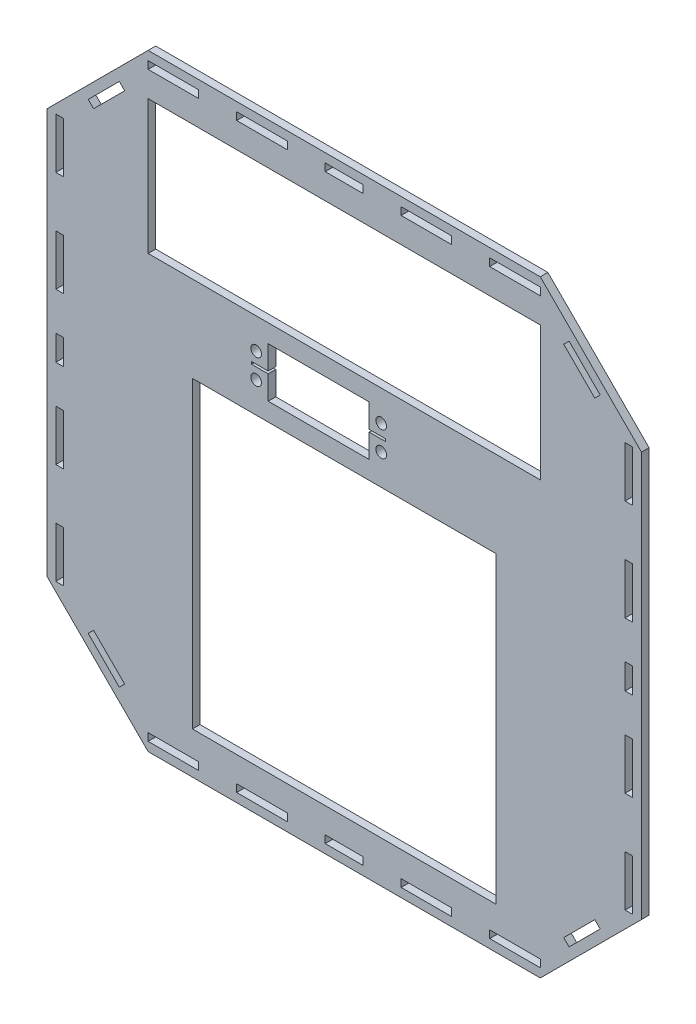
SolidWorks part; units mm, degrees
ref_plane "Přední rovina" through (0, 0, 0) normal (0, 0, 1) x (1, 0, 0)
ref_plane "Horní rovina" through (0, 0, 0) normal (0, 1, 0) x (1, 0, 0)
ref_plane "Pravá rovina" through (0, 0, 0) normal (1, 0, 0) x (0, 0, -1)
sketch "Skica2" plane through (0, 0, 0) normal (0, 0, 1) x (1, 0, 0)
  line L0 (-117.5, 80) -> (-77.5, 120)
  line L1 (-77.5, 120) -> (77.5, 120)
  line L2 (-117.5, 80) -> (-117.5, -80)
  line L3 (-77.5, -120) -> (77.5, -120)
  line L4 (117.5, 80) -> (117.5, -80)
  line L5 (-117.5, 120) -> (117.5, -120) construction
  line L6 (-117.5, -120) -> (117.5, 120) construction
  line L7 (77.5, 120) -> (117.5, 80)
  line L8 (77.5, -120) -> (117.5, -80)
  line L9 (-117.5, -80) -> (-77.5, -120)
  line L10 (0, 120) -> (0, -120) construction
  line L11 (-117.5, 0) -> (117.5, 0) construction
  line L21 (-111, 60) -> (-114, 60)
  line L22 (-114, 80) -> (-111, 80)
  line L23 (-114, 80) -> (-114, 60)
  line L25 (-111, 80) -> (-111, 60)
  line L26 (-114, 40) -> (-111, 40)
  line L27 (-114, 20) -> (-111, 20)
  line L28 (-114, 5) -> (-111, 5)
  line L29 (-111, 40) -> (-111, 20)
  line L30 (-114, 40) -> (-114, 20)
  line L31 (-111, 5) -> (-111, -5)
  line L32 (-114, 5) -> (-114, -5)
  line L33 (-114, -5) -> (-111, -5)
  line L34 (-114, -40) -> (-114, -20)
  line L35 (-114, -20) -> (-111, -20)
  line L36 (-111, -40) -> (-111, -20)
  line L37 (-114, -40) -> (-111, -40)
  line L38 (-114, -80) -> (-114, -60)
  line L39 (-111, -60) -> (-114, -60)
  line L40 (-111, -80) -> (-111, -60)
  line L41 (-114, -80) -> (-111, -80)
  line L42 (114, -80) -> (111, -80)
  line L43 (111, -80) -> (111, -60)
  line L44 (111, -60) -> (114, -60)
  line L45 (114, -80) -> (114, -60)
  line L46 (114, -40) -> (111, -40)
  line L47 (111, -40) -> (111, -20)
  line L48 (114, -20) -> (111, -20)
  line L49 (114, -40) -> (114, -20)
  line L50 (114, 5) -> (111, 5)
  line L51 (111, 5) -> (111, -5)
  line L52 (114, -5) -> (111, -5)
  line L53 (114, 5) -> (114, -5)
  line L54 (114, 40) -> (114, 20)
  line L55 (114, 20) -> (111, 20)
  line L56 (111, 40) -> (111, 20)
  line L57 (114, 40) -> (111, 40)
  line L58 (114, 80) -> (114, 60)
  line L59 (111, 60) -> (114, 60)
  line L60 (111, 80) -> (111, 60)
  line L61 (114, 80) -> (111, 80)
  line L62 (-57.5, 116.5) -> (-57.5, 113.5)
  line L63 (-77.5, 116.5) -> (-57.5, 116.5)
  line L64 (-77.5, 116.5) -> (-77.5, 113.5)
  line L65 (-77.5, 113.5) -> (-57.5, 113.5)
  line L67 (-42.5, 116.5) -> (-42.5, 113.5)
  line L68 (-22.5, 116.5) -> (-22.5, 113.5)
  line L69 (-7.5, 116.5) -> (-7.5, 113.5)
  line L70 (-42.5, 116.5) -> (-22.5, 116.5)
  line L71 (-42.5, 113.5) -> (-22.5, 113.5)
  line L72 (-7.5, 113.5) -> (7.5, 113.5)
  line L73 (-7.5, 116.5) -> (7.5, 116.5)
  line L74 (7.5, 116.5) -> (7.5, 113.5)
  line L75 (42.5, 116.5) -> (22.5, 116.5)
  line L76 (22.5, 116.5) -> (22.5, 113.5)
  line L77 (42.5, 113.5) -> (22.5, 113.5)
  line L78 (42.5, 116.5) -> (42.5, 113.5)
  line L79 (77.5, 116.5) -> (57.5, 116.5)
  line L80 (57.5, 116.5) -> (57.5, 113.5)
  line L81 (77.5, 113.5) -> (57.5, 113.5)
  line L82 (77.5, 116.5) -> (77.5, 113.5)
  line L83 (77.5, -116.5) -> (77.5, -113.5)
  line L84 (77.5, -113.5) -> (57.5, -113.5)
  line L85 (57.5, -116.5) -> (57.5, -113.5)
  line L86 (77.5, -116.5) -> (57.5, -116.5)
  line L87 (42.5, -116.5) -> (42.5, -113.5)
  line L88 (42.5, -113.5) -> (22.5, -113.5)
  line L89 (22.5, -116.5) -> (22.5, -113.5)
  line L90 (42.5, -116.5) -> (22.5, -116.5)
  line L91 (-7.5, -116.5) -> (-7.5, -113.5)
  line L92 (-7.5, -116.5) -> (7.5, -116.5)
  line L93 (7.5, -116.5) -> (7.5, -113.5)
  line L94 (-7.5, -113.5) -> (7.5, -113.5)
  line L95 (-42.5, -116.5) -> (-22.5, -116.5)
  line L96 (-22.5, -116.5) -> (-22.5, -113.5)
  line L97 (-42.5, -113.5) -> (-22.5, -113.5)
  line L98 (-42.5, -116.5) -> (-42.5, -113.5)
  line L99 (-77.5, -116.5) -> (-57.5, -116.5)
  line L100 (-57.5, -116.5) -> (-57.5, -113.5)
  line L101 (-77.5, -113.5) -> (-57.5, -113.5)
  line L102 (-77.5, -116.5) -> (-77.5, -113.5)
  line L103 (101.1685, -91.3817) -> (88.8817, -103.6685)
  line L104 (88.8817, -103.6685) -> (86.7604, -101.5472)
  line L105 (86.7604, -101.5472) -> (99.0472, -89.2604)
  line L106 (99.0472, -89.2604) -> (101.1685, -91.3817)
  line L107 (-86.7604, -101.5472) -> (-99.0472, -89.2604)
  line L108 (-88.8817, -103.6685) -> (-86.7604, -101.5472)
  line L109 (-101.1685, -91.3817) -> (-88.8817, -103.6685)
  line L110 (-99.0472, -89.2604) -> (-101.1685, -91.3817)
  line L111 (86.7604, 101.5472) -> (99.0472, 89.2604)
  line L112 (88.8817, 103.6685) -> (86.7604, 101.5472)
  line L113 (101.1685, 91.3817) -> (88.8817, 103.6685)
  line L114 (99.0472, 89.2604) -> (101.1685, 91.3817)
  line L115 (-88.8817, 103.6685) -> (-86.7604, 101.5472)
  line L116 (-101.1685, 91.3817) -> (-88.8817, 103.6685)
  line L117 (-99.0472, 89.2604) -> (-101.1685, 91.3817)
  line L118 (-86.7604, 101.5472) -> (-99.0472, 89.2604)
  line L126 (-77.5, 103.5) -> (77.5, 103.5)
  line L132 (-60, -103.5) -> (60, -103.5)
  line L133 (60, -103.5) -> (60, 16.5)
  line L134 (60, 16.5) -> (-60, 16.5)
  line L135 (-60, 16.5) -> (-60, -103.5)
  line L136 (77.5, 103.5) -> (77.5, 50.5)
  line L137 (77.5, 50.5) -> (-77.5, 50.5)
  line L138 (-77.5, 50.5) -> (-77.5, 103.5)
  line L139 (-30.05, 43.35) -> (-30.05, 33.975)
  line L143 (-30.05, 23.95) -> (-30.05, 43.05) construction
  line L144 (-36.1, 23.65) -> (-29.75, 23.65) construction
  line L145 (-29.75, 43.35) -> (-36.1, 43.35) construction
  line L146 (-30.05, 43.35) -> (9.85, 43.35)
  line L147 (15.9, 43.35) -> (9.55, 43.35) construction
  line L148 (9.85, 43.35) -> (9.85, 33.975)
  line L149 (9.55, 23.65) -> (15.9, 23.65) construction
  line L150 (9.85, 23.65) -> (-30.05, 23.65)
  line L152 (-30.05, 33.975) -> (-36.6, 33.975)
  line L153 (-36.6, 33.975) -> (-36.6, 33.025)
  line L154 (-36.6, 33.025) -> (-30.05, 33.025)
  line L155 (-30.05, 33.025) -> (-30.05, 23.65)
  line L156 (16.4, 33.975) -> (9.85, 33.975)
  line L157 (16.4, 33.975) -> (16.4, 33.025)
  line L158 (16.4, 33.025) -> (9.85, 33.025)
  line L159 (9.85, 33.025) -> (9.85, 23.65)
  circle A0 centre (14.6111, 38.425) radius 2.1
  circle A1 centre (14.6111, 28.575) radius 2.1
  circle A2 centre (-34.8111, 28.575) radius 2.1
  circle A3 centre (-34.8111, 38.425) radius 2.1
  point P0 (0, 0)
  point P57 (-114, 0)
  point P58 (-111, 0)
  point P101 (0, 113.5)
  point P102 (0, 116.5)
  dimension "D6" = 120
  dimension "D7" = 10
  dimension "D1" = 235
  dimension "D2" = 240
  dimension "D4" = 10
  dimension "D5" = 120
  dimension "D8" = 60
  dimension "D9" = 53
  dimension "D10" = 0
  dimension "D11" = 3
  dimension "D12" = 3.5
  dimension "D17" = 20
  dimension "D18" = 20
  dimension "D19" = 20
  dimension "D20" = 15
  dimension "D21" = 3.5
  dimension "D22" = 3
  dimension "D23" = 20
  dimension "D24" = 15
  dimension "D25" = 20
  dimension "D26" = 15
  dimension "D27" = 0
  dimension "D33" = 3
  dimension "D34" = 3.5
  dimension "D35" = 15
  dimension "D36" = 15
extrude "Přidat vysunutím1" add sketch "Skica2" along normal blind 3
